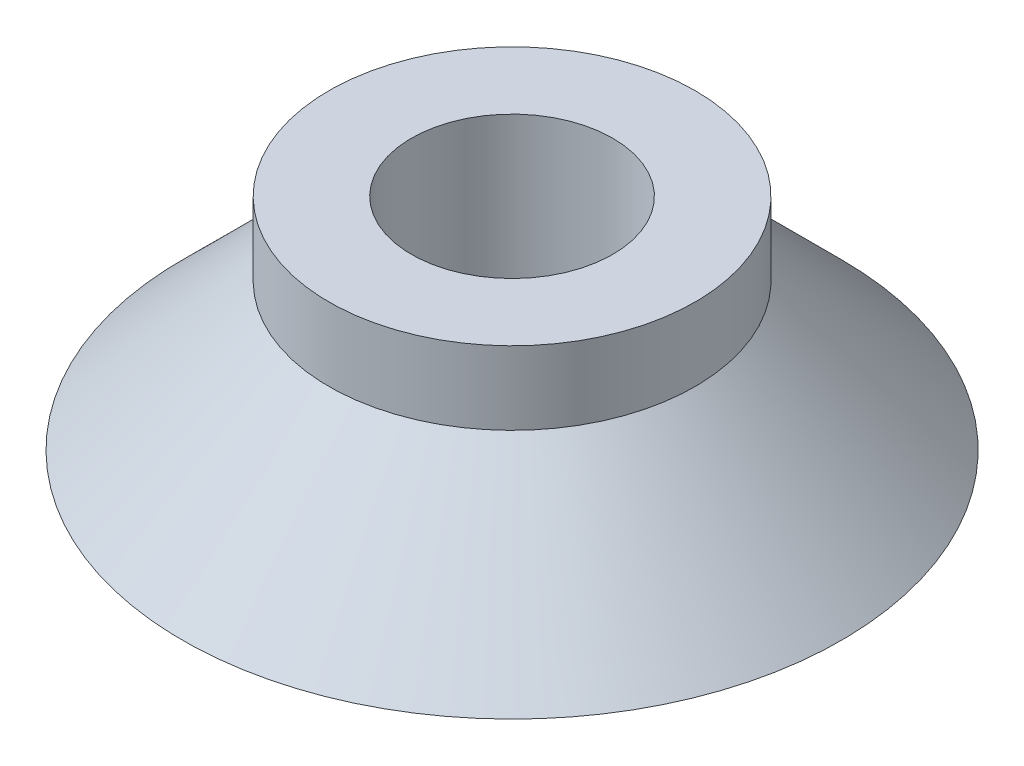
SolidWorks part; units mm, degrees
ref_plane "Спереди" through (0, 0, 0) normal (0, 0, 1) x (1, 0, 0)
ref_plane "Сверху" through (0, 0, 0) normal (0, 1, 0) x (1, 0, 0)
ref_plane "Справа" through (0, 0, 0) normal (1, 0, 0) x (0, 0, -1)
sketch "Эскиз1" plane through (0, 0, 0) normal (0, 0, 1) x (1, 0, 0)
  line L0 (5, 4) -> (9, 0)
  line L1 (0, 0) -> (5, 0)
  line L2 (0, 0) -> (0, 6)
  line L3 (0, 6) -> (5, 6)
  line L4 (5, 0) -> (5, 6)
  line L5 (9, 0) -> (5, 0)
  line L6 (2.75, 6) -> (2.75, 0)
  dimension "D1" = 45
  dimension "D2" = 5
  dimension "D3" = 2
  dimension "D4" = 2.75
  dimension "D5" = 6
revolve "Повернуть1" add sketch "Эскиз1" angle 360 about L2
